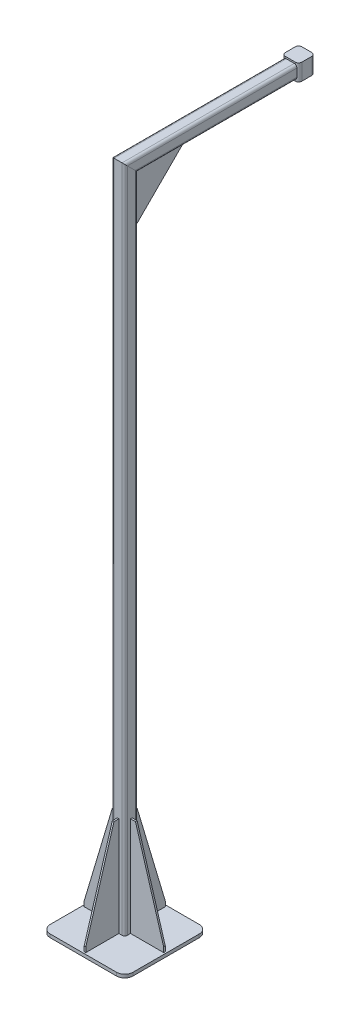
SolidWorks part; units mm, degrees
ref_plane "Front Plane" through (0, 0, 0) normal (0, 0, 1) x (1, 0, 0)
ref_plane "Top Plane" through (0, 0, 0) normal (0, 1, 0) x (1, 0, 0)
ref_plane "Right Plane" through (0, 0, 0) normal (1, 0, 0) x (0, 0, -1)
sketch "Sketch1" plane through (0, 0, 0) normal (0, 1, 0) x (1, 0, 0)
  line L1 (125, -125) -> (-125, -125)
  line L2 (125, -125) -> (125, 125)
  line L3 (125, 125) -> (-125, 125)
  line L4 (-125, -125) -> (-125, 125)
  line L5 (125, -125) -> (-125, 125) construction
  line L6 (125, 125) -> (-125, -125) construction
  point P0 (0, 0)
  dimension "D1" = 250
extrude "Boss-Extrude1" add sketch "Sketch1" along normal blind 10
sketch "Sketch2" plane through (0, 0, 0) normal (1, 0, 0) x (0, 0, -1)
  line L0 (0, 10) -> (0, 2010)
  line L1 (-125, 10) -> (125, 10) construction
  line L2 (0, 2010) -> (500, 2010)
  dimension "D1" = 2000
  dimension "D2" = 500
other "Square tube 40 X 40 X 4(1)"
ref_plane "Plane1" through (0, 10, 0) normal (0, 1, 0) x (0, 0, 1)
sketch "Sketch12" plane through (0, 10, 0) normal (0, 1, 0) x (0, 0, 1)
  line L0 (-12, -16) -> (12, -16)
  line L1 (-16, -12) -> (-16, 12)
  line L2 (12, 16) -> (-12, 16)
  line L3 (16, 12) -> (16, -12)
  line L4 (-12, -20) -> (12, -20)
  line L5 (-20, -12) -> (-20, 12)
  line L6 (12, 20) -> (-12, 20)
  line L7 (20, 12) -> (20, -12)
  arc A0 (20, 12) -> (12, 20) centre (12, 12) ccw
  arc A1 (12, -20) -> (20, -12) centre (12, -12) ccw
  arc A2 (-20, -12) -> (-12, -20) centre (-12, -12) ccw
  arc A3 (-12, 20) -> (-20, 12) centre (-12, 12) ccw
  arc A4 (-12, 16) -> (-16, 12) centre (-12, 12) ccw
  arc A5 (16, 12) -> (12, 16) centre (12, 12) ccw
  arc A6 (12, -16) -> (16, -12) centre (12, -12) ccw
  arc A7 (-16, -12) -> (-12, -16) centre (-12, -12) ccw
  point P0 (-20, 0)
  point P1 (20, 0)
  point P2 (0, 20)
  point P3 (0, -20)
  point P4 (0, 0)
  point P5 (-20, -20)
  point P6 (20, -20)
  point P7 (20, 20)
  point P8 (-20, 20)
  point P33 (0, 0)
  dimension "D1" = 8
  dimension "Thickness" = 4
  dimension "V_leg" = 40
other "Gusset1" parameters "D1"=5, "D2"=5, "D3"=0, "D4"=0, "D10"=5, "D11"=300, "D12"=100, "D13"=15, "D14"=73.393, "D15"=15
sketch "Sketch13" plane through (-20, 10, 0) normal (0, 0, 1) x (1, 0, 0)
  line L0 (0, 0) -> (0, 300)
  line L1 (0, 0) -> (-100, 0)
  line L2 (-15, 300) -> (-100, 15)
  line L3 (0, 300) -> (-15, 300)
  line L4 (-100, 0) -> (-100, 15)
other "Gusset2" parameters "D1"=5, "D2"=5, "D3"=0, "D4"=0, "D10"=5, "D11"=300, "D12"=100, "D13"=15, "D14"=73.393, "D15"=15
sketch "Sketch14" plane through (0, 10, -20) normal (-1, 0, 0) x (0, 0, 1)
  line L0 (0, 0) -> (0, 300)
  line L1 (0, 0) -> (-100, 0)
  line L2 (-15, 300) -> (-100, 15)
  line L3 (0, 300) -> (-15, 300)
  line L4 (-100, 0) -> (-100, 15)
other "Gusset3" parameters "D1"=5, "D2"=5, "D3"=0, "D4"=0, "D10"=5, "D11"=300, "D12"=100, "D13"=15, "D14"=73.393, "D15"=15
sketch "Sketch15" plane through (20, 10, 0) normal (0, 0, -1) x (-1, 0, 0)
  line L0 (0, 0) -> (0, 300)
  line L1 (0, 0) -> (-100, 0)
  line L2 (-15, 300) -> (-100, 15)
  line L3 (0, 300) -> (-15, 300)
  line L4 (-100, 0) -> (-100, 15)
other "Gusset4" parameters "D1"=5, "D2"=5, "D3"=0, "D4"=0, "D10"=5, "D11"=300, "D12"=100, "D13"=15, "D14"=73.393, "D15"=15
sketch "Sketch16" plane through (0, 10, 20) normal (1, 0, 0) x (0, 0, -1)
  line L0 (0, 0) -> (0, 300)
  line L1 (0, 0) -> (-100, 0)
  line L2 (-15, 300) -> (-100, 15)
  line L3 (0, 300) -> (-15, 300)
  line L4 (-100, 0) -> (-100, 15)
other "Gusset5" parameters "D1"=5, "D2"=5, "D3"=0, "D4"=0, "D10"=5, "D11"=150, "D12"=150, "D13"=15, "D14"=45, "D15"=15
sketch "Sketch17" plane through (0, 1990, -20) normal (-1, 0, 0) x (0, 0, 1)
  line L0 (0, 0) -> (-150, 0)
  line L1 (0, 0) -> (0, -150)
  line L2 (-150, -15) -> (-15, -150)
  line L3 (-150, 0) -> (-150, -15)
  line L4 (0, -150) -> (-15, -150)
sketch "Sketch18" plane through (0, 0, -500) normal (0, 0, -1) x (-1, 0, 0)
  line L0 (-14.8284, 2024.8284) -> (14.8284, 1995.1716) construction
  line L2 (25, 1985) -> (-25, 1985)
  line L3 (25, 1985) -> (25, 2035)
  line L4 (25, 2035) -> (-25, 2035)
  line L5 (-25, 1985) -> (-25, 2035)
  line L6 (25, 1985) -> (-25, 2035) construction
  line L7 (25, 2035) -> (-25, 1985) construction
  arc A0 (-12, 2026) -> (-16, 2022) centre (-12, 2022) ccw construction
  arc A1 (12, 1994) -> (16, 1998) centre (12, 1998) ccw construction
  point P8 (0, 2010)
  dimension "D1" = 50
extrude "Boss-Extrude2" add sketch "Sketch18" along normal blind 50 separate body
fillet "Fillet1" radius 10 4 edges at (25, 2010, -500) (25, 2010, -550) (-25, 2010, -500) (-25, 2010, -550)
fillet "Fillet2" radius 25 4 edges at (125, 5, 125) (-125, 5, 125) (125, 5, -125) (-125, 5, -125)
ref_plane "Plane2" through (0, 0, -525) normal (0, 0, -1) x (-1, 0, 0)
